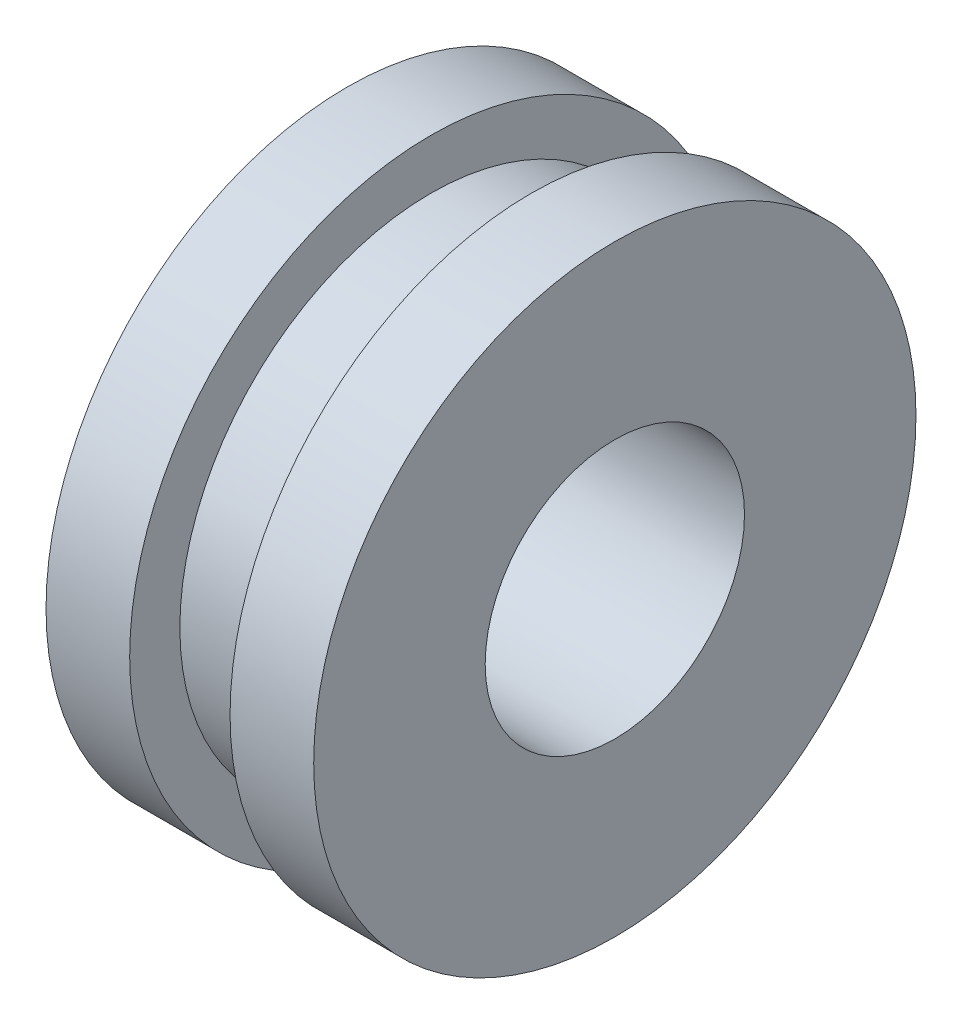
SolidWorks part; units mm, degrees
ref_plane "Front Plane" through (0, 0, 0) normal (0, 0, 1) x (1, 0, 0)
ref_plane "Top Plane" through (0, 0, 0) normal (0, 1, 0) x (1, 0, 0)
ref_plane "Right Plane" through (0, 0, 0) normal (1, 0, 0) x (0, 0, -1)
sketch "Sketch1" plane through (0, 0, 0) normal (0, 0, 1) x (1, 0, 0)
  line L0 (0, 0) -> (5.1881, 0) construction
  line L1 (-4, 2) -> (4, 2)
  line L2 (-4, 2) -> (-4, 10)
  line L3 (-4, 10) -> (4, 10)
  line L4 (4, 2) -> (4, 10)
  dimension "D1" = 10
  dimension "D2" = 8
  dimension "D3" = 2
  dimension "D4" = 4
revolve "Revolve1" add sketch "Sketch1" angle 360 about L0
sketch "Sketch2" plane through (0, 0, 0) normal (0, 0, 1) x (1, 0, 0)
  line L0 (-4, 10) -> (-4, -10) construction
  line L1 (-4, -10) -> (-4, 0) construction
  line L2 (-4, 0) -> (4, 0) construction
  line L3 (4, -10) -> (4, 10) construction
  line L4 (-4, 4.5) -> (-3.25, 4.5)
  line L5 (-3.25, 4.5) -> (-3.25, 3.875)
  line L6 (-3.25, 3.875) -> (4, 3.875)
  line L7 (4, 3.875) -> (4, 1.375)
  line L8 (4, 1.375) -> (-4, 1.375)
  line L9 (-4, 1.375) -> (-4, 4.5)
  dimension "D1" = 1.375
  dimension "D2" = 3.875
  dimension "D3" = 4.5
  dimension "D4" = 0.75
revolve "Cut-Revolve1" cut sketch "Sketch2" angle 360 about L2
sketch "Sketch5" plane through (0, 0, 0) normal (0, 0, 1) x (1, 0, 0)
  line L0 (-5.6933, 11) -> (6.0917, 11)
  line L1 (6.0917, 11) -> (6.0917, 9)
  line L2 (6.0917, 9) -> (1.5, 9)
  line L3 (1.5, 9) -> (1.5, 7.5)
  line L4 (1.5, 7.5) -> (-1.5, 7.5)
  line L5 (-1.5, 7.5) -> (-1.5, 9)
  line L6 (-1.5, 9) -> (-5.6933, 9)
  line L7 (-5.6933, 9) -> (-5.6933, 11)
  line L8 (-5.6933, 0) -> (7.2558, 0) construction
  line L11 (4, -10) -> (4, 10) construction
  point P2 (0, 7.5)
  dimension "D1" = 11
  dimension "D2" = 9
  dimension "D3" = 3
  dimension "D4" = 7.5
revolve "Cut-Revolve2" cut sketch "Sketch5" angle 360 about L8
